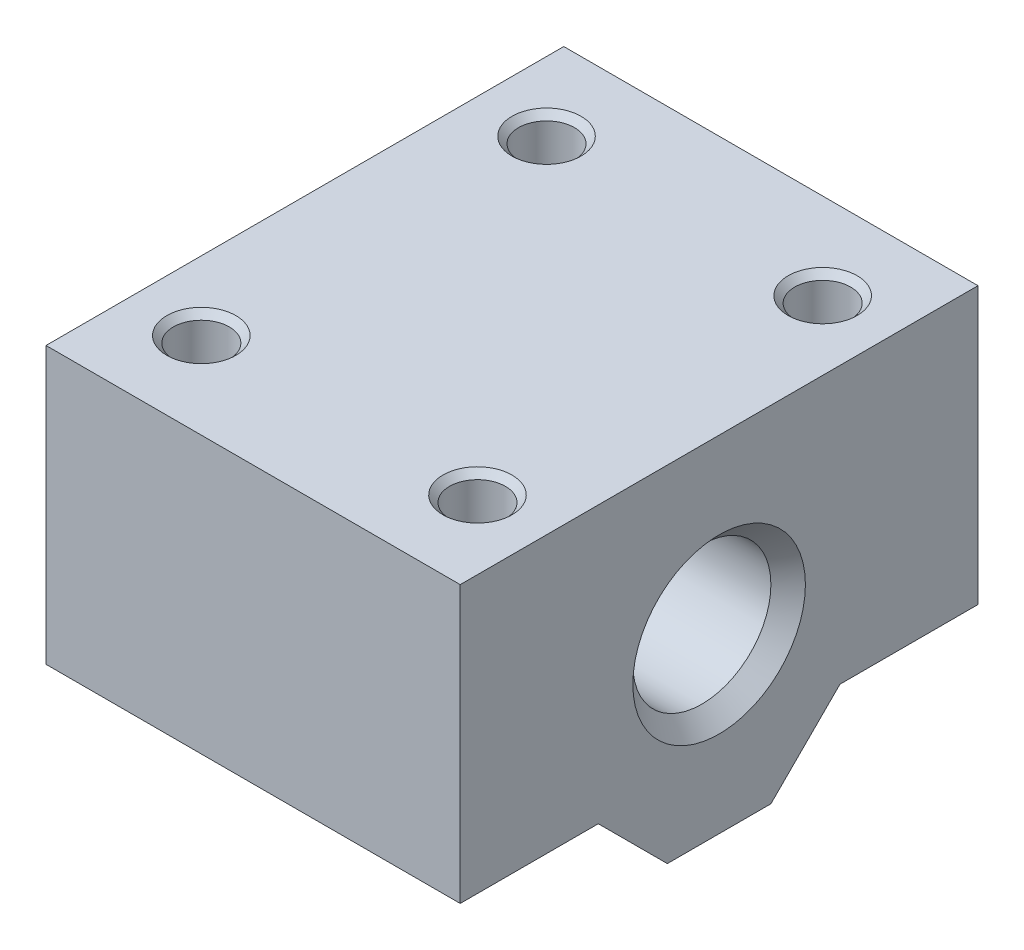
SolidWorks part; units mm, degrees
ref_plane "Plan de face" through (0, 0, 0) normal (0, 0, 1) x (1, 0, 0)
ref_plane "Plan de dessus" through (0, 0, 0) normal (0, 1, 0) x (1, 0, 0)
ref_plane "Plan de droite" through (0, 0, 0) normal (1, 0, 0) x (0, 0, -1)
ref_plane "Plan1" through (0, 10, 0) normal (0, 1, 0) x (1, 0, 0)
sketch "Esquisse1" plane through (0, 10, 0) normal (0, 1, 0) x (1, 0, 0)
  line L0 (0, 15) -> (0, -15)
  line L1 (0, -15) -> (24, -15)
  line L2 (24, -15) -> (24, 15)
  line L3 (24, 15) -> (0, 15)
extrude "Boss.-Extru.1" add sketch "Esquisse1" against normal blind 20
sketch "Esquisse2" plane through (24, 0, 0) normal (1, 0, 0) x (0, 0, -1)
  line L0 (15, -10) -> (15, -6)
  line L1 (15, -6) -> (3, -6)
  line L2 (3, -6) -> (3, -10)
  line L3 (3, -10) -> (15, -10)
extrude "Enlèv. mat.-Extru.1" cut sketch "Esquisse2" against normal through all
sketch "Esquisse3" plane through (24, 0, 0) normal (1, 0, 0) x (0, 0, -1)
  line L0 (-3, -10) -> (-3, -6)
  line L1 (-3, -6) -> (-15, -6)
  line L2 (-15, -6) -> (-15, -10)
  line L3 (-15, -10) -> (-3, -10)
extrude "Enlèv. mat.-Extru.2" cut sketch "Esquisse3" against normal through all
draft "Dépouille1" type of draft neutral plane draft angle 45 faces to draft 2 face at (12, -8, -3) face at (12, -8, 3) neutral plane through (0, -10, 0) neutral plane normal (0, -1, 0) parameters "D1"=45
hole_wizard "Diamètre du perçage Ø8.0 (8)1" positions "Esquisse5" profile "Esquisse4" hole size "Ø8.0" standard "Ansi Metric"
sketch "Esquisse5" plane through (0, 0, 0) normal (-1, 0, 0) x (0, 0, 1)
  point P0 (0, 0)
sketch "Esquisse4" plane through (0, 0, 0) normal (0, 1, 0) x (0, 0, 1)
  line L0 (0, 0) -> (0, 24)
  line L1 (0, 24) -> (4, 24)
  line L2 (4, 24) -> (4, 0)
  line L5 (4, 0) -> (0, 0)
  line L11 (0, -6.35) -> (0, 107.95) construction
  dimension "Diamètre du perçage jusqu'au prochain" = 8
  dimension "Profondeur du perçage jusqu'au prochain" = 24
hole_wizard "Dégagement M31" positions "Esquisse7" profile "Esquisse6" hole size "M3" standard "Ansi Metric"
sketch "Esquisse7" plane through (0, 10, 0) normal (0, 1, 0) x (1, 0, 0)
  point P0 (20, -10)
  point P1 (4, -10)
  point P2 (4, 10)
  point P3 (20, 10)
sketch "Esquisse6" plane through (20, 10, 10) normal (1, 0, 0) x (0, 0, 1)
  line L0 (0, 0) -> (0, 20)
  line L1 (0, 20) -> (1.621, 20)
  line L2 (1.621, 20) -> (1.621, 0)
  line L5 (1.621, 0) -> (0, 0)
  line L11 (0, -6.35) -> (0, 107.95) construction
  dimension "Diamètre du perçage jusqu'au prochain" = 3.242
  dimension "Profondeur du perçage jusqu'au prochain" = 20
chamfer "Chanfrein1" distance 0.379 angle 45 4 edges at (20, 10, -8.379) (4, 10, 11.621) (20, 10, 11.621) (4, 10, -8.379)
chamfer "Chanfrein2" distance 1 angle 45 2 edges at (24, 0, 4) (0, 0, 4)
